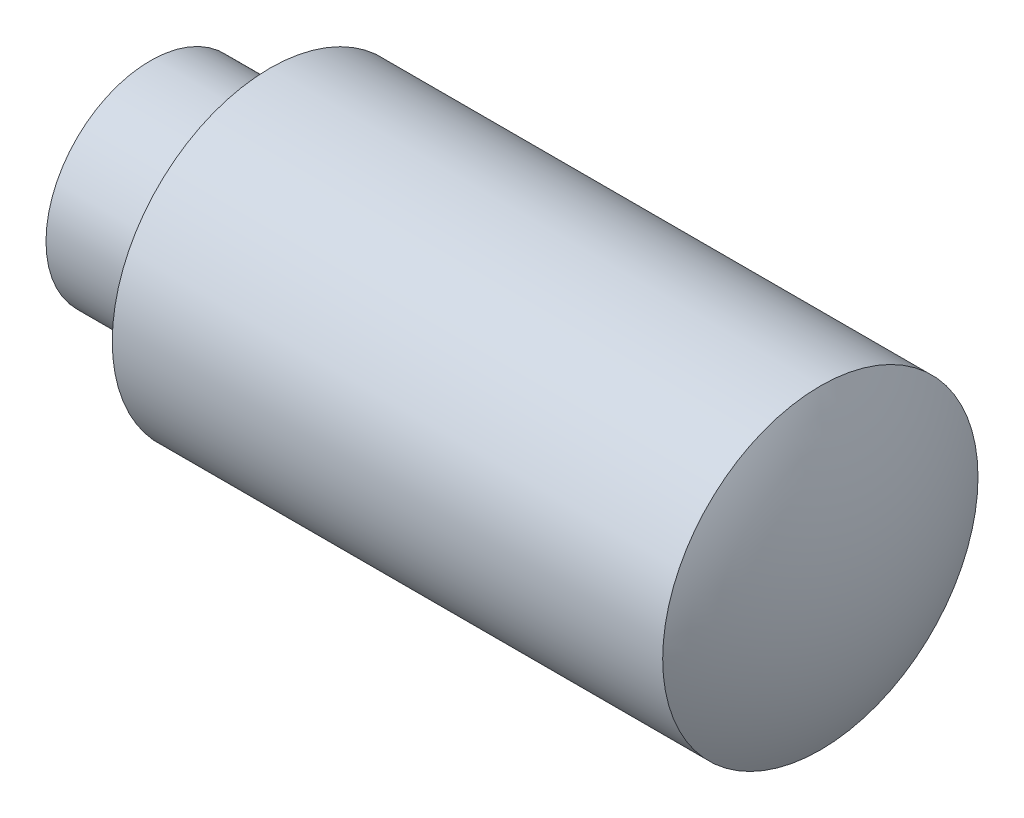
SolidWorks part; units mm, degrees
ref_plane "前视基准面" through (0, 0, 0) normal (0, 0, 1) x (1, 0, 0)
ref_plane "上视基准面" through (0, 0, 0) normal (0, 1, 0) x (1, 0, 0)
ref_plane "右视基准面" through (0, 0, 0) normal (1, 0, 0) x (0, 0, -1)
sketch "草图1" plane through (0, 0, 0) normal (0, 0, 1) x (1, 0, 0)
  line L0 (-2.2068, 0.6696) -> (-2.2068, -0.6696) construction
  line L1 (-1.4129, 0.6929) -> (-1.4129, -0.6929) construction
  line L2 (-1.4129, 0.6929) -> (-2.2068, 0.6929)
  line L3 (-2.2068, 0.6929) -> (-2.2068, 0.6696)
  line L4 (-1.4129, -0.6929) -> (-2.2068, -0.6929)
  line L5 (-2.2068, -0.6929) -> (-2.2068, -0.6696)
  line L6 (-2.3062, 0) -> (-1.0656, 0) construction
  line L7 (2.2418, 1.0468) -> (2.2418, -1.0468) construction
  line L8 (2.2418, 1.0468) -> (-1.4129, 1.0468)
  line L9 (-1.4129, 1.0468) -> (-1.4129, 0.6929)
  line L10 (2.2418, -1.0468) -> (-1.4129, -1.0468)
  line L11 (-1.4129, -1.0468) -> (-1.4129, -0.6929)
  line L12 (-1.0656, 0) -> (2.5206, 0) construction
  arc A0 (-2.2068, 0.6696) -> (-2.2068, -0.6696) centre (0, 0) ccw
  arc A1 (-1.4129, -0.6929) -> (-1.4129, 0.6929) centre (-1.9304, 0) ccw
  arc A2 (2.2418, -1.0468) -> (2.2418, 1.0468) centre (0.4158, 0) ccw
  point P5 (-2.3062, 0)
  point P14 (2.5206, 0)
  point P17 (-1.0656, 0)
  dimension "D1" = 0.6696
  dimension "D2" = 0.6929
  dimension "D4" = 0.8648
  dimension "D3" = 2.3062
  dimension "D7" = 2.1048
  dimension "D5" = 1.2405
  dimension "D6" = 1.0468
  dimension "D8" = 3.5862
sketch "草图2" plane through (0, 0, 0) normal (0, 0, 1) x (1, 0, 0)
  line L0 (-1.4129, -1.0468) -> (-1.4129, -0.6929) construction
  line L1 (2.2418, -1.0468) -> (-1.4129, -1.0468) construction
  line L2 (2.2418, 1.0468) -> (-1.4129, 1.0468) construction
  line L3 (-1.4129, 1.0468) -> (-1.4129, 0.6929) construction
  line L4 (-1.4129, -1.0468) -> (-1.4129, -0.6929)
  line L5 (2.2418, -1.0468) -> (-1.4129, -1.0468)
  line L6 (2.2418, 1.0468) -> (-1.4129, 1.0468)
  line L7 (-1.4129, 1.0468) -> (-1.4129, 0.6929)
  line L8 (-1.0656, 0) -> (2.5206, 0) construction
  arc A0 (2.2418, -1.0468) -> (2.2418, 1.0468) centre (0.4158, 0) ccw construction
  arc A1 (-1.4129, -0.6929) -> (-1.4129, 0.6929) centre (-1.9304, 0) ccw construction
  arc A2 (2.2418, -1.0468) -> (2.2418, 1.0468) centre (0.4158, 0) ccw
  arc A3 (-1.4129, -0.6929) -> (-1.4129, 0.6929) centre (-1.9304, 0) ccw
sketch "草图3" plane through (0, 0, 0) normal (0, 0, 1) x (1, 0, 0)
  line L0 (-1.4129, -0.6929) -> (-2.2068, -0.6929) construction
  line L1 (-2.2068, 0.6929) -> (-2.2068, 0.6696) construction
  line L2 (-1.4129, 0.6929) -> (-2.2068, 0.6929) construction
  line L3 (-1.4129, -0.6929) -> (-2.2068, -0.6929)
  line L4 (-2.2068, 0.6929) -> (-2.2068, 0.6696)
  line L5 (-1.4129, 0.6929) -> (-2.2068, 0.6929)
  line L6 (-2.3062, 0) -> (-1.0656, 0) construction
  line L7 (-2.2068, -0.6929) -> (-2.2068, -0.6696)
  arc A0 (-1.4129, -0.6929) -> (-1.4129, 0.6929) centre (-1.9304, 0) ccw construction
  arc A1 (-2.2068, 0.6696) -> (-2.2068, -0.6696) centre (0, 0) ccw construction
  arc A2 (-1.4129, -0.6929) -> (-1.4129, 0.6929) centre (-1.9304, 0) ccw
  arc A3 (-2.2068, 0.6696) -> (-2.2068, -0.6696) centre (0, 0) ccw
revolve "旋转3" add sketch "草图2" angle 360 about L8
revolve "旋转5" add sketch "草图3" angle 360 about L6
